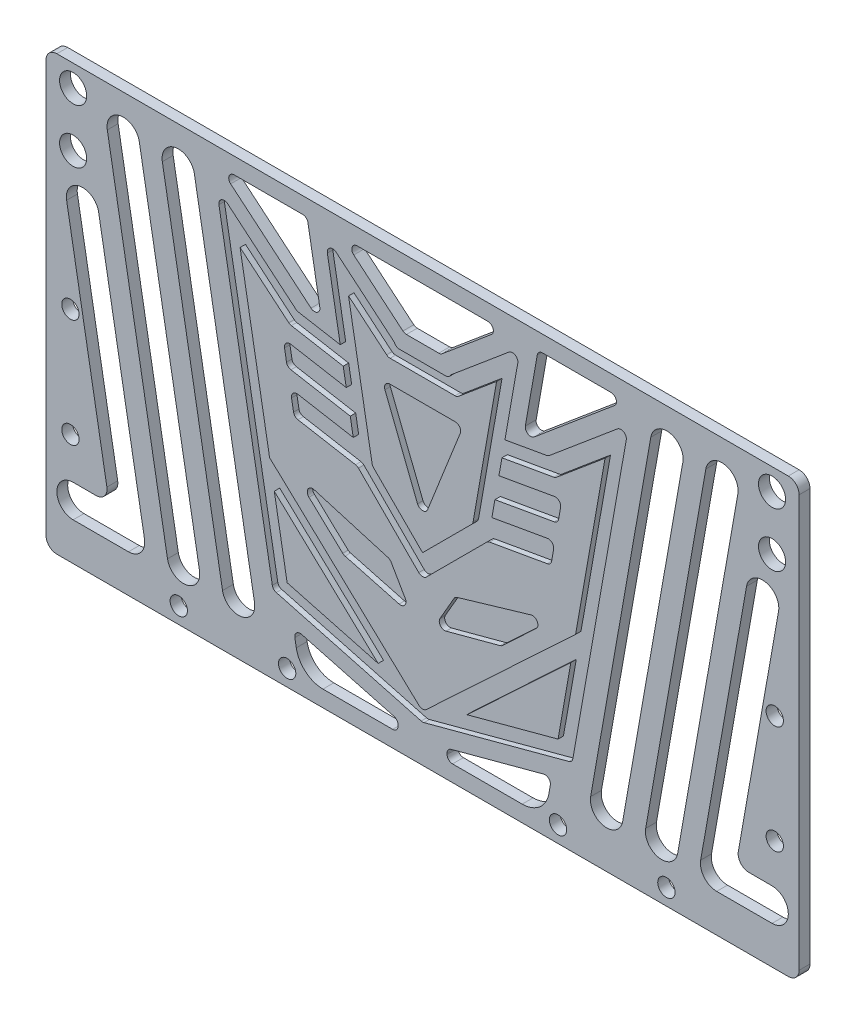
SolidWorks part; units mm, degrees
material "Thornel Mat VMA"
ref_plane "前视基准面" through (0, 0, 0) normal (0, 0, 1) x (1, 0, 0)
ref_plane "上视基准面" through (0, 0, 0) normal (0, 1, 0) x (1, 0, 0)
ref_plane "右视基准面" through (0, 0, 0) normal (1, 0, 0) x (0, 0, -1)
sketch "草图1" plane through (0, 0, 0) normal (0, 0, 1) x (1, 0, 0)
  line L1 (-69.5, 40) -> (69.5, 40)
  line L2 (-69.5, 40) -> (-69.5, -40)
  line L3 (-69.5, -40) -> (69.5, -40)
  line L4 (69.5, 40) -> (69.5, -40)
  line L5 (-69.5, 40) -> (69.5, -40) construction
  line L6 (-69.5, -40) -> (69.5, 40) construction
  point P0 (0, 0)
  dimension "D1" = 139
  dimension "D2" = 80
extrude "凸台-拉伸1" add sketch "草图1" along normal blind 2
sketch "草图2" plane through (0, 0, 0) normal (0, 0, -1) x (-1, 0, 0)
  circle A0 centre (-45, -37) radius 1.6
  circle A1 centre (-25, -37) radius 1.6
  circle A2 centre (25, -37) radius 1.6
  circle A3 centre (45, -37) radius 1.6
  dimension "D1" = 3.2
extrude "切除-拉伸1" cut sketch "草图2" against normal blind 10
sketch "草图3" plane through (0, 0, 0) normal (0, 0, -1) x (-1, 0, 0)
  line L1 (-1.3397, -15) -> (-51.3397, -15)
  line L2 (-1.3397, -15) -> (-18.6603, 15)
  line L6 (-35, 0) -> (-35, 16.5) construction
  line L7 (-35, 0) -> (-49.2894, -8.25) construction
  line L8 (-35, 0) -> (-20.7106, -8.25) construction
  line L9 (-35, 2.6) -> (-30.2, 2.6) construction
  line L10 (-35, 0) -> (-30.2, 0) construction
  line L11 (-35, 0) -> (-35, 6.6) construction
  line L12 (-35, 6.6) -> (-30.2, 6.6) construction
  line L13 (-30.2, 0) -> (-30.2, 6.6) construction
  line L14 (-51.3397, -15) -> (-68.6603, 15)
  line L15 (-18.6603, 15) -> (-68.6603, 15)
  line L16 (-32.3909, -3.9037) -> (-35, 0) construction
  line L17 (-39.6853, -0.3077) -> (-35, 0) construction
  line L18 (-32.9238, 4.2114) -> (-35, 0) construction
  line L19 (-33.3265, -4.3035) -> (-34.5582, -2.4607)
  line L20 (-31.394, -3.5956) -> (-32.8954, -1.3493)
  line L21 (-39.9169, -1.3251) -> (-37.2208, -1.148)
  line L22 (-39.5637, 0.7024) -> (-37.3519, 0.8477)
  line L23 (-33.6891, 4.9207) -> (-34.8838, 2.4973)
  line L24 (-32.1098, 3.6011) -> (-33.0899, 1.6129)
  circle A0 centre (-35, 0) radius 16.5
  arc A3 (-35, 6.6) -> (-30.2, 2.6) centre (-26.586, 11.8168) ccw
  arc A4 (-33.3058, 16.4128) -> (-35, 6.6) centre (-28.6258, 10.5521) ccw
  arc A5 (-21.9598, -10.1096) -> (-30.2, 2.6) centre (-34.9456, -9.5028) ccw
  arc A6 (-21.6332, -9.6736) -> (-29.2842, -3.3) centre (-29.0487, -10.7963) ccw
  arc A7 (-50.2752, -6.2384) -> (-35.1483, -5.4569) centre (-43.2569, 4.7043) ccw
  arc A8 (-29.2842, -3.3) -> (-35.1483, -5.4569) centre (-28.9734, -13.1951) ccw
  arc A9 (-50.061, -6.7391) -> (-40.7158, -3.3) centre (-47.3255, 0.2442) ccw
  arc A10 (-32.765, 16.3479) -> (-39.6517, 2.8569) centre (-26.7975, 4.7985) ccw
  arc A11 (-40.7158, -3.3) -> (-39.6517, 2.8569) centre (-49.4406, 1.3783) ccw
  circle A12 centre (-35, 0) radius 2.5
  point P0 (-10, 0)
  point P43 (-35, 0)
  dimension "D6" = 33
  dimension "D10" = 19.8
  dimension "D11" = 15
  dimension "D12" = 26
  dimension "D16" = 5
  dimension "D2" = 50
  dimension "D3" = 30
  dimension "D4" = 60
  dimension "D5" = 120
  dimension "D7" = 4.8
  dimension "D8" = 6.6
  dimension "D9" = 2.6
  dimension "D14" = 10
  dimension "D15" = 35
  dimension "D17" = 2
  dimension "D18" = 2
  dimension "D19" = 2
  dimension "D13" = 3
extrude "切除-拉伸2" [suppressed] cut sketch "草图3" against normal blind 10 contours A0 L15 L14 L1 | A0 L1 L2 L15 | A12 L23 A3 A4 L15 A10 A11 L22 | A12 L21 A11 A9 A7 A8 L19 | A12 L20 A8 A6 A5 A3 L24
mirror "镜向1" [suppressed] about plane through (0, 0, 0) normal (1, 0, 0)
sketch "草图7" plane through (0, 0, 2) normal (0, 0, 1) x (1, 0, 0)
  line L0 (-7.5, 6.6144) -> (-1.5, 34.9678)
  line L1 (0, 10) -> (0, 51.6967) construction
  line L2 (7.5, 6.6144) -> (1.5, 34.9678)
  line L3 (0, 0) -> (24.9019, 9.0635)
  line L4 (0, 0) -> (72.3407, 0) construction
  line L5 (7.5, 6.6144) -> (4.826, 5.0705)
  line L6 (9.4782, 3.188) -> (6.8042, 1.6441)
  line L7 (0, 0) -> (8.6603, 5) construction
  line L8 (-1.9782, -9.8024) -> (-1.9782, -6.7147)
  line L9 (1.9782, -9.8024) -> (1.9782, -6.7147)
  line L10 (-7.5, 6.6144) -> (-4.826, 5.0705)
  line L11 (1.9782, -9.8024) -> (29.533, -18.783)
  line L12 (9.4782, 3.188) -> (31.033, -16.1849)
  line L13 (-9.4782, 3.188) -> (-31.033, -16.1849)
  line L14 (-1.9782, -9.8024) -> (-29.533, -18.783)
  line L15 (-9.4782, 3.188) -> (-6.8042, 1.6441)
  circle A0 centre (0, 0) radius 35
  circle A1 centre (0, 0) radius 26.5
  circle A2 centre (0, 0) radius 25
  circle A3 centre (0, 0) radius 10
  arc A5 (24.9019, 9.0635) -> (1.5, 34.9678) centre (-4.9044, 5.6594) ccw
  circle A6 centre (0, 0) radius 7
  arc A7 (-4.6017, -26.0974) -> (29.533, -18.783) centre (7.3534, 1.4176) ccw
  arc A8 (-20.3002, 17.0339) -> (-31.033, -16.1849) centre (-2.449, -7.077) ccw
  point P30 (0, 0)
  point P31 (0, 0)
  point P44 (0, 0)
  dimension "D1" = 70
  dimension "D2" = 53
  dimension "D3" = 50
  dimension "D4" = 20
  dimension "D7" = 30
  dimension "D9" = 3
  dimension "D5" = 15
  dimension "D6" = 3
  dimension "D8" = 20
  dimension "D11" = 3
  dimension "D10" = 3
extrude "切除-拉伸3" [suppressed] cut sketch "草图7" against normal blind 3 contours A1 A8 L13 | A1 L13 A0 L14 | A2 L13 A1 L14 | A3 L13 A2 L14 | A6 L15 A3 L8 | A6 L9 A3 L6 | A3 L11 A2 L12 | A2 L11 A1 L12 | A1 L11 A0 L12 | A1 A7 L11 | A6 L5 A3 L10 | A3 L2 A2 L0 | A2 L2 A1 L0 | A1 L2 A0 L0 | A1 A5 L2
sketch "草图8" plane through (0, 0, 2) normal (0, 0, 1) x (1, 0, 0)
  line L0 (-33.6824, 25.9391) -> (-25, -23.3013)
  line L1 (-25, -23.3013) -> (0, -30)
  line L2 (0, -30) -> (25, -23.3013)
  line L3 (25, -23.3013) -> (33.6824, 25.9391)
  line L4 (33.6824, 25.9391) -> (24.4899, 18.2257)
  line L5 (24.4899, 18.2257) -> (11.5, 15.9352)
  line L6 (11.5, 15.9352) -> (13.6634, 28.2047)
  line L7 (13.6634, 28.2047) -> (5, 20.9352)
  line L8 (5, 20.9352) -> (-5, 20.9352)
  line L9 (-5, 20.9352) -> (-13.6634, 28.2047)
  line L10 (-13.6634, 28.2047) -> (-11.5, 15.9352)
  line L11 (-11.5, 15.9352) -> (-24.4899, 18.2257)
  line L12 (-24.4899, 18.2257) -> (-33.6824, 25.9391)
  line L13 (0, 31.1727) -> (0, 81.1727) construction
  line L14 (-69.5, -40) -> (69.5, -40) construction
  line L15 (0, -30) -> (28.5265, -3.3013)
  line L16 (0, -30) -> (-28.5265, -3.3013)
  line L17 (2.0505, -29.4506) -> (28.2373, -4.9416)
  line L18 (8.2018, -27.8023) -> (27.3696, -9.8627)
  line L19 (-2.0505, -29.4506) -> (-28.2373, -4.9416)
  line L20 (-8.2018, -27.8023) -> (-27.3696, -9.8627)
  line L21 (11.5, 15.9352) -> (9.2661, 3.2661)
  line L22 (9.2661, 3.2661) -> (0, -6)
  line L23 (0, -6) -> (-9.2661, 3.2661)
  line L24 (-9.2661, 3.2661) -> (-11.5, 15.9352)
  line L25 (14.644, 16.4896) -> (12.0563, 1.8136)
  line L26 (12.0563, 1.8136) -> (0, -10.2426)
  line L27 (-14.644, 16.4896) -> (-12.0563, 1.8136)
  line L28 (-12.0563, 1.8136) -> (0, -10.2426)
  line L29 (14.089, 13.3417) -> (25.7305, 15.3945)
  line L30 (25.7305, 15.3945) -> (24.9914, 11.2024)
  line L31 (24.9914, 11.2024) -> (13.3498, 9.1497)
  line L32 (12.7954, 6.0057) -> (24.437, 8.0584)
  line L33 (24.437, 8.0584) -> (23.6978, 3.8663)
  line L34 (23.6978, 3.8663) -> (12.0563, 1.8136)
  line L35 (2, -17) -> (14.5573, -13.6362)
  line L36 (14.5573, -13.6362) -> (24.0487, -4.7529)
  line L37 (24.0487, -4.7529) -> (6.0005, -10.0721)
  line L38 (6.0005, -10.0721) -> (2, -17)
  line L39 (0, 0) -> (41.7879, 0) construction
  line L40 (-24.0487, -4.7529) -> (-6.0005, -10.0721)
  line L41 (-14.5573, -13.6362) -> (-24.0487, -4.7529)
  line L42 (-2, -17) -> (-14.5573, -13.6362)
  line L43 (-6.0005, -10.0721) -> (-2, -17)
  line L44 (-23.6978, 3.8663) -> (-12.0563, 1.8136)
  line L45 (-24.437, 8.0584) -> (-23.6978, 3.8663)
  line L46 (-12.7954, 6.0057) -> (-24.437, 8.0584)
  line L47 (-25.7305, 15.3945) -> (-24.9914, 11.2024)
  line L48 (-14.089, 13.3417) -> (-25.7305, 15.3945)
  line L49 (-24.9914, 11.2024) -> (-13.3498, 9.1497)
  line L50 (12.0544, 19.0792) -> (23.1773, 21.0405)
  line L51 (23.1773, 21.0405) -> (38.0681, 33.5354)
  line L52 (38.0681, 33.5354) -> (33.9182, 10)
  line L53 (-33.9182, 10) -> (-30.8719, 10)
  line L54 (-23.1773, 21.0405) -> (-38.0681, 33.5354)
  line L55 (-12.0544, 19.0792) -> (-23.1773, 21.0405)
  line L56 (33.9182, 10) -> (30.8719, 10)
  line L57 (-38.0681, 33.5354) -> (-33.9182, 10)
  line L58 (25, -23.3013) -> (24.4252, -26.5611)
  line L59 (24.4252, -26.5611) -> (2.0505, -32.5564)
  line L60 (2.0505, -29.4506) -> (2.0505, -32.5564)
  line L61 (-25, -23.3013) -> (-24.4252, -26.5611)
  line L62 (-24.4252, -26.5611) -> (-2.0505, -32.5564)
  line L63 (-2.0505, -32.5564) -> (-2.0505, -29.4506)
  line L64 (28.2373, -4.9416) -> (31.8857, -1.527)
  line L65 (31.8857, -1.527) -> (29.1574, -17)
  line L66 (29.1574, -17) -> (26.1111, -17)
  line L67 (-29.1574, -17) -> (-26.1111, -17)
  line L68 (-31.8857, -1.527) -> (-29.1574, -17)
  line L69 (-28.2373, -4.9416) -> (-31.8857, -1.527)
  line L70 (-15.1984, 19.6336) -> (-18.0491, 35.801)
  line L71 (-18.0491, 35.801) -> (-5, 24.8514)
  line L72 (-5, 24.8514) -> (-5, 20.9352)
  line L73 (5, 24.8514) -> (5, 20.9352)
  line L74 (15.1984, 19.6336) -> (18.0491, 35.801)
  line L75 (18.0491, 35.801) -> (5, 24.8514)
  dimension "D1" = 150
  dimension "D2" = 115
  dimension "D3" = 40
  dimension "D4" = 150
  dimension "D5" = 50
  dimension "D6" = 10
  dimension "D7" = 50
  dimension "D8" = 12
  dimension "D9" = 23
  dimension "D10" = 5
  dimension "D11" = 10
  dimension "D12" = 20
  dimension "D13" = 1
  dimension "D14" = 3
  dimension "D15" = 6
  dimension "D16" = 90
  dimension "D17" = 3
  dimension "D18" = 3
  dimension "D19" = 4
  dimension "D20" = 4
  dimension "D21" = 3
  dimension "D22" = 6
  dimension "D23" = 2
  dimension "D24" = 45
  dimension "D25" = 8
  dimension "D26" = 13
  dimension "D27" = 3
  dimension "D28" = 13
  dimension "D29" = 3
  dimension "D30" = 3
  dimension "D31" = 3
  dimension "D32" = 3
  dimension "D33" = 3
  dimension "D34" = 17
  dimension "D35" = 3
  dimension "D36" = 10
  dimension "D37" = 17
extrude "切除-拉伸4" cut sketch "草图8" against normal blind 10
sketch "草图10" plane through (0, 0, 2) normal (0, 0, 1) x (1, 0, 0)
  line L7 (-7.5, 17.9352) -> (7.5, 17.9352)
  line L10 (7.5, 17.9352) -> (0, -1)
  line L11 (0, -1) -> (-7.5, 17.9352)
  line L12 (0, 0) -> (0, 45.0401) construction
  dimension "D1" = 5
  dimension "D2" = 15
  dimension "D3" = 3
extrude "切除-拉伸6" cut sketch "草图10" against normal blind 10
sketch "草图12" plane through (0, 0, 0) normal (0, 0, -1) x (-1, 0, 0)
  line L0 (-45.0817, 33) -> (-33.9731, -30) construction
  line L1 (-42.1273, 33.5209) -> (-31.0187, -29.4791)
  line L2 (-48.0361, 32.4791) -> (-36.9275, -30.5209)
  line L3 (-55.236, 33) -> (-44.1274, -30) construction
  line L4 (-52.2815, 33.5209) -> (-41.1729, -29.4791)
  line L5 (-58.1904, 32.4791) -> (-47.0818, -30.5209)
  line L6 (-62.7453, 18) -> (-54.2816, -30) construction
  line L7 (-59.7909, 18.5209) -> (-51.3272, -29.4791)
  line L8 (-65.6997, 17.4791) -> (-57.8569, -27)
  line L9 (-31.8857, -1.527) -> (-29.1574, -17) construction
  line L10 (69.5, -40) -> (-69.5, -40) construction
  line L11 (-69.5, 40) -> (69.5, 40) construction
  line L12 (-69.5, -40) -> (-69.5, 40) construction
  line L15 (-54.2816, -30) -> (-64.5, -30) construction
  line L16 (-54.2816, -33) -> (-64.5, -33)
  line L18 (-57.8569, -27) -> (-64.5, -27)
  line L19 (0, -52.9402) -> (0, 55.6243) construction
  line L20 (45.0817, 33) -> (33.9731, -30) construction
  line L21 (42.1273, 33.5209) -> (31.0187, -29.4791)
  line L22 (48.0361, 32.4791) -> (36.9275, -30.5209)
  line L23 (55.236, 33) -> (44.1274, -30) construction
  line L24 (52.2815, 33.5209) -> (41.1729, -29.4791)
  line L25 (58.1904, 32.4791) -> (47.0818, -30.5209)
  line L26 (54.2816, -30) -> (64.5, -30) construction
  line L27 (62.7453, 18) -> (54.2816, -30) construction
  line L28 (57.8569, -27) -> (64.5, -27)
  line L29 (54.2816, -33) -> (64.5, -33)
  line L30 (65.6997, 17.4791) -> (57.8569, -27)
  line L31 (59.7909, 18.5209) -> (51.3272, -29.4791)
  arc A0 (-42.1273, 33.5209) -> (-48.0361, 32.4791) centre (-45.0817, 33) ccw
  arc A1 (-36.9275, -30.5209) -> (-31.0187, -29.4791) centre (-33.9731, -30) ccw
  arc A2 (-52.2815, 33.5209) -> (-58.1904, 32.4791) centre (-55.236, 33) ccw
  arc A3 (-47.0818, -30.5209) -> (-41.1729, -29.4791) centre (-44.1274, -30) ccw
  arc A4 (-59.7909, 18.5209) -> (-65.6997, 17.4791) centre (-62.7453, 18) ccw
  arc A5 (-54.2816, -33) -> (-51.3272, -29.4791) centre (-54.2816, -30) ccw
  circle A8 centre (-64.5, 26) radius 2.5
  circle A9 centre (-64.5, 36) radius 2.5
  arc A10 (-54.2816, -33) -> (-51.3272, -29.4791) centre (-54.2816, -30) ccw
  arc A11 (-64.5, -27) -> (-64.5, -33) centre (-64.5, -30) ccw
  arc A12 (42.1273, 33.5209) -> (48.0361, 32.4791) centre (45.0817, 33) cw
  arc A13 (36.9275, -30.5209) -> (31.0187, -29.4791) centre (33.9731, -30) cw
  arc A14 (52.2815, 33.5209) -> (58.1904, 32.4791) centre (55.236, 33) cw
  arc A15 (47.0818, -30.5209) -> (41.1729, -29.4791) centre (44.1274, -30) cw
  arc A16 (64.5, -27) -> (64.5, -33) centre (64.5, -30) cw
  arc A17 (54.2816, -33) -> (51.3272, -29.4791) centre (54.2816, -30) cw
  circle A18 centre (64.5, 36) radius 2.5
  circle A19 centre (64.5, 26) radius 2.5
  arc A20 (54.2816, -33) -> (51.3272, -29.4791) centre (54.2816, -30) cw
  arc A21 (59.7909, 18.5209) -> (65.6997, 17.4791) centre (62.7453, 18) cw
  point P2 (-39.5274, 1.5)
  point P7 (-49.6817, 1.5)
  point P34 (39.5274, 1.5)
  point P48 (49.6817, 1.5)
  dimension "D2" = 3
  dimension "D8" = 5
  dimension "D12" = 2
  dimension "D13" = 3
  dimension "D1" = 10
  dimension "D3" = 7
  dimension "D4" = 4
  dimension "D5" = 4
  dimension "D6" = 4
  dimension "D7" = 22
  dimension "D9" = 5
  dimension "D10" = 10
  dimension "D11" = 4
  dimension "D14" = 45.1652
  dimension "D15" = 6
extrude "切除-拉伸7" cut sketch "草图12" against normal blind 10 contours A21 L31 A17 L29 A16 L28 L30 | A15 L25 A14 L24 | A13 L22 A12 L21 | A18 | A19 | L5 A3 L4 A2 | L2 A1 L1 A0 | A8 | A9 | L18 A11 L16 A5 L7 A4 L8
fillet "圆角2" radius 1 36 edges at (7.5, 17.9352, 1) (-7.5, 17.9352, 1) (0, -1, 1) (33.9182, 10, 1) (30.8719, 10, 1) (38.0681, 33.5354, 1) (18.0491, 35.801, 1) (5, 24.8514, 1) (5, 20.9352, 1) (-5, 20.9352, 1) (-5, 24.8514, 1) (-18.0491, 35.801, 1) (-24.4899, 18.2257, 1) (-38.0681, 33.5354, 1) (-33.9182, 10, 1) (-30.8719, 10, 1) (-24.9914, 11.2024, 1) (-25.7305, 15.3945, 1) (-24.437, 8.0584, 1) (-23.6978, 3.8663, 1) (25.7305, 15.3945, 1) (24.9914, 11.2024, 1) (24.437, 8.0584, 1) (23.6978, 3.8663, 1) (0, -10.2426, 1) (-2, -17, 1) (-14.5573, -13.6362, 1) (-24.0487, -4.7529, 1) (-6.0005, -10.0721, 1) (14.5573, -13.6362, 1) (2, -17, 1) (6.0005, -10.0721, 1) (24.0487, -4.7529, 1) (-23.1773, 21.0405, 1) (23.1773, 21.0405, 1) (24.4899, 18.2257, 1)
sketch "草图16" plane through (0, 0, 0) normal (0, 0, -1) x (-1, 0, 0)
  line L3 (-6.9581, 16.5669) -> (-0.9297, 1.3473)
  line L4 (5.8006, -10.4182) -> (3.2072, -14.9093)
  line L5 (20.0041, -5.9449) -> (6.3839, -9.9591)
  line L6 (14.74, -13.4651) -> (20.9701, -7.6342)
  line L7 (4.332, -16.3753) -> (14.3155, -13.7009)
  line L8 (5.8006, -10.4182) -> (3.2072, -14.9093)
  line L9 (8.2018, -27.8023) -> (27.3696, -9.8627)
  line L10 (25, -23.3013) -> (8.2018, -27.8023)
  line L11 (24.4252, -26.5611) -> (25, -23.3013)
  line L12 (2.0505, -32.5564) -> (24.4252, -26.5611)
  line L13 (2.0505, -29.4506) -> (2.0505, -32.5564)
  line L14 (31.8857, -1.527) -> (2.0505, -29.4506)
  line L15 (29.1574, -17) -> (31.8857, -1.527)
  line L16 (26.1111, -17) -> (29.1574, -17)
  line L17 (27.3696, -9.8627) -> (26.1111, -17)
  line L18 (8.2018, -27.8023) -> (27.3696, -9.8627)
  line L19 (25, -23.3013) -> (8.2018, -27.8023)
  line L20 (24.4252, -26.5611) -> (25, -23.3013)
  line L21 (2.0505, -32.5564) -> (24.4252, -26.5611)
  line L22 (2.0505, -29.4506) -> (2.0505, -32.5564)
  line L23 (31.8857, -1.527) -> (2.0505, -29.4506)
  line L24 (29.1574, -17) -> (31.8857, -1.527)
  line L25 (26.1111, -17) -> (29.1574, -17)
  line L26 (27.3696, -9.8627) -> (26.1111, -17)
  line L27 (20.0041, -5.9449) -> (6.3839, -9.9591)
  line L28 (14.74, -13.4651) -> (20.9701, -7.6342)
  line L29 (4.332, -16.3753) -> (14.3155, -13.7009)
  line L30 (-14.3155, -13.7009) -> (-4.332, -16.3753)
  line L31 (-20.9701, -7.6342) -> (-14.74, -13.4651)
  line L32 (-6.3839, -9.9591) -> (-20.0041, -5.9449)
  line L33 (-3.2072, -14.9093) -> (-5.8006, -10.4182)
  line L34 (-14.3155, -13.7009) -> (-4.332, -16.3753)
  line L35 (-20.9701, -7.6342) -> (-14.74, -13.4651)
  line L36 (-6.3839, -9.9591) -> (-20.0041, -5.9449)
  line L37 (-3.2072, -14.9093) -> (-5.8006, -10.4182)
  line L38 (6.0283, 17.9352) -> (-6.0283, 17.9352)
  line L39 (0.9297, 1.3473) -> (6.9581, 16.5669)
  line L40 (-6.9581, 16.5669) -> (-0.9297, 1.3473)
  line L41 (6.0283, 17.9352) -> (-6.0283, 17.9352)
  line L42 (0.9297, 1.3473) -> (6.9581, 16.5669)
  line L43 (-2.0505, -29.4506) -> (-31.8857, -1.527)
  line L44 (-2.0505, -32.5564) -> (-2.0505, -29.4506)
  line L45 (-24.4252, -26.5611) -> (-2.0505, -32.5564)
  line L46 (-25, -23.3013) -> (-24.4252, -26.5611)
  line L47 (-8.2018, -27.8023) -> (-25, -23.3013)
  line L48 (-27.3696, -9.8627) -> (-8.2018, -27.8023)
  line L49 (-26.1111, -17) -> (-27.3696, -9.8627)
  line L50 (-29.1574, -17) -> (-26.1111, -17)
  line L51 (-31.8857, -1.527) -> (-29.1574, -17)
  line L52 (-2.0505, -29.4506) -> (-31.8857, -1.527)
  line L53 (-2.0505, -32.5564) -> (-2.0505, -29.4506)
  line L54 (-24.4252, -26.5611) -> (-2.0505, -32.5564)
  line L55 (-25, -23.3013) -> (-24.4252, -26.5611)
  line L56 (-8.2018, -27.8023) -> (-25, -23.3013)
  line L57 (-27.3696, -9.8627) -> (-8.2018, -27.8023)
  line L58 (-26.1111, -17) -> (-27.3696, -9.8627)
  line L59 (-29.1574, -17) -> (-26.1111, -17)
  line L60 (-31.8857, -1.527) -> (-29.1574, -17)
  line L96 (22.9134, 20.994) -> (15.1984, 19.6336)
  line L97 (35.9634, 31.7693) -> (23.3826, 21.2127)
  line L98 (34.0639, 10.8264) -> (37.591, 30.8296)
  line L99 (32.0637, 10) -> (33.0791, 10)
  line L100 (33.6824, 25.9391) -> (31.0789, 11.1736)
  line L101 (24.6951, 18.3979) -> (33.6824, 25.9391)
  line L102 (14.644, 16.4896) -> (24.226, 18.1791)
  line L103 (14.089, 13.3417) -> (14.644, 16.4896)
  line L104 (24.3241, 15.1465) -> (14.089, 13.3417)
  line L105 (25.113, 11.892) -> (25.4825, 13.988)
  line L106 (13.3498, 9.1497) -> (24.3018, 11.0808)
  line L107 (12.7954, 6.0057) -> (13.3498, 9.1497)
  line L108 (23.0305, 7.8104) -> (12.7954, 6.0057)
  line L109 (23.8194, 4.5559) -> (24.189, 6.6519)
  line L110 (12.0563, 1.8136) -> (23.0083, 3.7448)
  line L111 (0.7071, -9.5355) -> (12.0563, 1.8136)
  line L112 (-12.0563, 1.8136) -> (-0.7071, -9.5355)
  line L113 (-23.0083, 3.7448) -> (-12.0563, 1.8136)
  line L114 (-24.189, 6.6519) -> (-23.8194, 4.5559)
  line L115 (-12.7954, 6.0057) -> (-23.0305, 7.8104)
  line L116 (-13.3498, 9.1497) -> (-12.7954, 6.0057)
  line L117 (-24.3018, 11.0808) -> (-13.3498, 9.1497)
  line L118 (-25.4825, 13.988) -> (-25.113, 11.892)
  line L119 (-14.089, 13.3417) -> (-24.3241, 15.1465)
  line L120 (-14.644, 16.4896) -> (-14.089, 13.3417)
  line L121 (-24.226, 18.1791) -> (-14.644, 16.4896)
  line L122 (-33.6824, 25.9391) -> (-24.6951, 18.3979)
  line L123 (-31.0789, 11.1736) -> (-33.6824, 25.9391)
  line L124 (-33.0791, 10) -> (-32.0637, 10)
  line L125 (-37.591, 30.8296) -> (-34.0639, 10.8264)
  line L126 (-23.3826, 21.2127) -> (-35.9634, 31.7693)
  line L127 (-15.1984, 19.6336) -> (-22.9134, 20.994)
  line L128 (-17.5721, 33.0952) -> (-15.1984, 19.6336)
  line L129 (-5.3572, 25.1512) -> (-15.9445, 34.0349)
  line L130 (-5, 23.0797) -> (-5, 24.3851)
  line L131 (-13.6634, 28.2047) -> (-6.6428, 22.3137)
  line L132 (-9.2661, 3.2661) -> (-13.6634, 28.2047)
  line L133 (0, -6) -> (-9.2661, 3.2661)
  line L134 (9.2661, 3.2661) -> (0, -6)
  line L135 (13.6634, 28.2047) -> (9.2661, 3.2661)
  line L136 (6.6428, 22.3137) -> (13.6634, 28.2047)
  line L137 (5, 24.3851) -> (5, 23.0797)
  line L138 (15.9445, 34.0349) -> (5.3572, 25.1512)
  line L139 (15.1984, 19.6336) -> (17.5721, 33.0952)
  line L140 (22.9134, 20.994) -> (15.1984, 19.6336)
  line L141 (35.9634, 31.7693) -> (23.3826, 21.2127)
  line L142 (34.0639, 10.8264) -> (37.591, 30.8296)
  line L143 (32.0637, 10) -> (33.0791, 10)
  line L144 (33.6824, 25.9391) -> (31.0789, 11.1736)
  line L145 (24.6951, 18.3979) -> (33.6824, 25.9391)
  line L146 (14.644, 16.4896) -> (24.226, 18.1791)
  line L147 (14.089, 13.3417) -> (14.644, 16.4896)
  line L148 (24.3241, 15.1465) -> (14.089, 13.3417)
  line L149 (25.113, 11.892) -> (25.4825, 13.988)
  line L150 (13.3498, 9.1497) -> (24.3018, 11.0808)
  line L151 (12.7954, 6.0057) -> (13.3498, 9.1497)
  line L152 (23.0305, 7.8104) -> (12.7954, 6.0057)
  line L153 (23.8194, 4.5559) -> (24.189, 6.6519)
  line L154 (12.0563, 1.8136) -> (23.0083, 3.7448)
  line L155 (0.7071, -9.5355) -> (12.0563, 1.8136)
  line L156 (-12.0563, 1.8136) -> (-0.7071, -9.5355)
  line L157 (-23.0083, 3.7448) -> (-12.0563, 1.8136)
  line L158 (-24.189, 6.6519) -> (-23.8194, 4.5559)
  line L159 (-12.7954, 6.0057) -> (-23.0305, 7.8104)
  line L160 (-13.3498, 9.1497) -> (-12.7954, 6.0057)
  line L161 (-24.3018, 11.0808) -> (-13.3498, 9.1497)
  line L162 (-25.4825, 13.988) -> (-25.113, 11.892)
  line L163 (-14.089, 13.3417) -> (-24.3241, 15.1465)
  line L164 (-14.644, 16.4896) -> (-14.089, 13.3417)
  line L165 (-24.226, 18.1791) -> (-14.644, 16.4896)
  line L166 (-33.6824, 25.9391) -> (-24.6951, 18.3979)
  line L167 (-31.0789, 11.1736) -> (-33.6824, 25.9391)
  line L168 (-33.0791, 10) -> (-32.0637, 10)
  line L169 (-37.591, 30.8296) -> (-34.0639, 10.8264)
  line L170 (-23.3826, 21.2127) -> (-35.9634, 31.7693)
  line L171 (-15.1984, 19.6336) -> (-22.9134, 20.994)
  line L172 (-17.5721, 33.0952) -> (-15.1984, 19.6336)
  line L173 (-5.3572, 25.1512) -> (-15.9445, 34.0349)
  line L174 (-5, 23.0797) -> (-5, 24.3851)
  line L175 (-13.6634, 28.2047) -> (-6.6428, 22.3137)
  line L176 (-9.2661, 3.2661) -> (-13.6634, 28.2047)
  line L177 (0, -6) -> (-9.2661, 3.2661)
  line L178 (9.2661, 3.2661) -> (0, -6)
  line L179 (13.6634, 28.2047) -> (9.2661, 3.2661)
  line L180 (6.6428, 22.3137) -> (13.6634, 28.2047)
  line L181 (5, 24.3851) -> (5, 23.0797)
  line L182 (15.9445, 34.0349) -> (5.3572, 25.1512)
  line L183 (15.1984, 19.6336) -> (17.5721, 33.0952)
  arc A3 (-6.0283, 17.9352) -> (-6.9581, 16.5669) centre (-6.0283, 16.9352) ccw
  arc A4 (6.3839, -9.9591) -> (5.8006, -10.4182) centre (6.6666, -10.9183) ccw
  arc A5 (20.9701, -7.6342) -> (20.0041, -5.9449) centre (20.2867, -6.9041) ccw
  arc A6 (14.3155, -13.7009) -> (14.74, -13.4651) centre (14.0567, -12.735) ccw
  arc A7 (3.2072, -14.9093) -> (4.332, -16.3753) centre (4.0732, -15.4094) ccw
  arc A8 (6.3839, -9.9591) -> (5.8006, -10.4182) centre (6.6666, -10.9183) ccw
  arc A9 (20.9701, -7.6342) -> (20.0041, -5.9449) centre (20.2867, -6.9041) ccw
  arc A10 (14.3155, -13.7009) -> (14.74, -13.4651) centre (14.0567, -12.735) ccw
  arc A11 (3.2072, -14.9093) -> (4.332, -16.3753) centre (4.0732, -15.4094) ccw
  arc A12 (-14.74, -13.4651) -> (-14.3155, -13.7009) centre (-14.0567, -12.735) ccw
  arc A13 (-20.0041, -5.9449) -> (-20.9701, -7.6342) centre (-20.2867, -6.9041) ccw
  arc A14 (-5.8006, -10.4182) -> (-6.3839, -9.9591) centre (-6.6666, -10.9183) ccw
  arc A15 (-4.332, -16.3753) -> (-3.2072, -14.9093) centre (-4.0732, -15.4094) ccw
  arc A16 (-14.74, -13.4651) -> (-14.3155, -13.7009) centre (-14.0567, -12.735) ccw
  arc A17 (-20.0041, -5.9449) -> (-20.9701, -7.6342) centre (-20.2867, -6.9041) ccw
  arc A18 (-5.8006, -10.4182) -> (-6.3839, -9.9591) centre (-6.6666, -10.9183) ccw
  arc A19 (-4.332, -16.3753) -> (-3.2072, -14.9093) centre (-4.0732, -15.4094) ccw
  arc A20 (6.9581, 16.5669) -> (6.0283, 17.9352) centre (6.0283, 16.9352) ccw
  arc A21 (-0.9297, 1.3473) -> (0.9297, 1.3473) centre (0, 1.7155) ccw
  arc A22 (-6.0283, 17.9352) -> (-6.9581, 16.5669) centre (-6.0283, 16.9352) ccw
  arc A23 (6.9581, 16.5669) -> (6.0283, 17.9352) centre (6.0283, 16.9352) ccw
  arc A24 (-0.9297, 1.3473) -> (0.9297, 1.3473) centre (0, 1.7155) ccw
  arc A41 (22.9134, 20.994) -> (23.3826, 21.2127) centre (22.7398, 21.9788) ccw
  arc A42 (37.591, 30.8296) -> (35.9634, 31.7693) centre (36.6062, 31.0033) ccw
  arc A43 (33.0791, 10) -> (34.0639, 10.8264) centre (33.0791, 11) ccw
  arc A44 (31.0789, 11.1736) -> (32.0637, 10) centre (32.0637, 11) ccw
  arc A45 (24.226, 18.1791) -> (24.6951, 18.3979) centre (24.0523, 19.1639) ccw
  arc A46 (25.4825, 13.988) -> (24.3241, 15.1465) centre (24.4977, 14.1617) ccw
  arc A47 (24.3018, 11.0808) -> (25.113, 11.892) centre (24.1282, 12.0656) ccw
  arc A48 (24.189, 6.6519) -> (23.0305, 7.8104) centre (23.2042, 6.8256) ccw
  arc A49 (23.0083, 3.7448) -> (23.8194, 4.5559) centre (22.8346, 4.7296) ccw
  arc A50 (-0.7071, -9.5355) -> (0.7071, -9.5355) centre (0, -8.8284) ccw
  arc A51 (-23.8194, 4.5559) -> (-23.0083, 3.7448) centre (-22.8346, 4.7296) ccw
  arc A52 (-23.0305, 7.8104) -> (-24.189, 6.6519) centre (-23.2042, 6.8256) ccw
  arc A53 (-25.113, 11.892) -> (-24.3018, 11.0808) centre (-24.1282, 12.0656) ccw
  arc A54 (-24.3241, 15.1465) -> (-25.4825, 13.988) centre (-24.4977, 14.1617) ccw
  arc A55 (-24.6951, 18.3979) -> (-24.226, 18.1791) centre (-24.0523, 19.1639) ccw
  arc A56 (-32.0637, 10) -> (-31.0789, 11.1736) centre (-32.0637, 11) ccw
  arc A57 (-34.0639, 10.8264) -> (-33.0791, 10) centre (-33.0791, 11) ccw
  arc A58 (-35.9634, 31.7693) -> (-37.591, 30.8296) centre (-36.6062, 31.0033) ccw
  arc A59 (-23.3826, 21.2127) -> (-22.9134, 20.994) centre (-22.7398, 21.9788) ccw
  arc A60 (-15.9445, 34.0349) -> (-17.5721, 33.0952) centre (-16.5872, 33.2689) ccw
  arc A61 (-5, 24.3851) -> (-5.3572, 25.1512) centre (-6, 24.3851) ccw
  arc A62 (-6.6428, 22.3137) -> (-5, 23.0797) centre (-6, 23.0797) ccw
  arc A63 (5, 23.0797) -> (6.6428, 22.3137) centre (6, 23.0797) ccw
  arc A64 (5.3572, 25.1512) -> (5, 24.3851) centre (6, 24.3851) ccw
  arc A65 (17.5721, 33.0952) -> (15.9445, 34.0349) centre (16.5872, 33.2689) ccw
  arc A66 (22.9134, 20.994) -> (23.3826, 21.2127) centre (22.7398, 21.9788) ccw
  arc A67 (37.591, 30.8296) -> (35.9634, 31.7693) centre (36.6062, 31.0033) ccw
  arc A68 (33.0791, 10) -> (34.0639, 10.8264) centre (33.0791, 11) ccw
  arc A69 (31.0789, 11.1736) -> (32.0637, 10) centre (32.0637, 11) ccw
  arc A70 (24.226, 18.1791) -> (24.6951, 18.3979) centre (24.0523, 19.1639) ccw
  arc A71 (25.4825, 13.988) -> (24.3241, 15.1465) centre (24.4977, 14.1617) ccw
  arc A72 (24.3018, 11.0808) -> (25.113, 11.892) centre (24.1282, 12.0656) ccw
  arc A73 (24.189, 6.6519) -> (23.0305, 7.8104) centre (23.2042, 6.8256) ccw
  arc A74 (23.0083, 3.7448) -> (23.8194, 4.5559) centre (22.8346, 4.7296) ccw
  arc A75 (-0.7071, -9.5355) -> (0.7071, -9.5355) centre (0, -8.8284) ccw
  arc A76 (-23.8194, 4.5559) -> (-23.0083, 3.7448) centre (-22.8346, 4.7296) ccw
  arc A77 (-23.0305, 7.8104) -> (-24.189, 6.6519) centre (-23.2042, 6.8256) ccw
  arc A78 (-25.113, 11.892) -> (-24.3018, 11.0808) centre (-24.1282, 12.0656) ccw
  arc A79 (-24.3241, 15.1465) -> (-25.4825, 13.988) centre (-24.4977, 14.1617) ccw
  arc A80 (-24.6951, 18.3979) -> (-24.226, 18.1791) centre (-24.0523, 19.1639) ccw
  arc A81 (-32.0637, 10) -> (-31.0789, 11.1736) centre (-32.0637, 11) ccw
  arc A82 (-34.0639, 10.8264) -> (-33.0791, 10) centre (-33.0791, 11) ccw
  arc A83 (-35.9634, 31.7693) -> (-37.591, 30.8296) centre (-36.6062, 31.0033) ccw
  arc A84 (-23.3826, 21.2127) -> (-22.9134, 20.994) centre (-22.7398, 21.9788) ccw
  arc A85 (-15.9445, 34.0349) -> (-17.5721, 33.0952) centre (-16.5872, 33.2689) ccw
  arc A86 (-5, 24.3851) -> (-5.3572, 25.1512) centre (-6, 24.3851) ccw
  arc A87 (-6.6428, 22.3137) -> (-5, 23.0797) centre (-6, 23.0797) ccw
  arc A88 (5, 23.0797) -> (6.6428, 22.3137) centre (6, 23.0797) ccw
  arc A89 (5.3572, 25.1512) -> (5, 24.3851) centre (6, 24.3851) ccw
  arc A90 (17.5721, 33.0952) -> (15.9445, 34.0349) centre (16.5872, 33.2689) ccw
  dimension "D1" = 0
  dimension "D2" = 0
  dimension "D3" = 0
  dimension "D4" = 0
  dimension "D5" = 0
  dimension "D6" = 0
extrude "凸台-拉伸7" add sketch "草图16" against normal blind 1
sketch "草图17" plane through (0, 0, 2) normal (0, 0, 1) x (1, 0, 0)
  line L0 (-33.6824, 25.9391) -> (-36.6368, 25.4182)
  line L1 (-37.591, 30.8296) -> (-34.0639, 10.8264) construction
  line L2 (-36.6368, 25.4182) -> (-27.6225, -25.7044)
  line L3 (-27.6225, -25.7044) -> (-24.4252, -26.5611)
  line L4 (-24.4252, -26.5611) -> (-33.6824, 25.9391)
  line L5 (2.0505, -29.4506) -> (0, -31.3697)
  line L6 (0, -31.3697) -> (-2.0505, -29.4506)
  line L7 (-2.0505, -29.4506) -> (-2.0505, -32.5564)
  line L8 (-2.0505, -32.5564) -> (0, -33.1058)
  line L9 (0, -33.1058) -> (2.0505, -32.5564)
  line L10 (2.0505, -32.5564) -> (2.0505, -29.4506)
  line L11 (-6, 22.0797) -> (6, 22.0797)
  line L12 (-5, 24.3851) -> (5, 24.3851)
  line L13 (-6, 22.0797) -> (-6, 24.3851)
  line L14 (-6, 24.3851) -> (-5, 24.3851)
  line L15 (6, 22.0797) -> (6, 24.3851)
  line L16 (6, 24.3851) -> (5, 24.3851)
  line L17 (-24.4252, -26.5611) -> (-2.0505, -32.5564) construction
  line L18 (24.4252, -26.5611) -> (2.0505, -32.5564) construction
  line L19 (-2.0505, -29.4506) -> (-31.8857, -1.527) construction
  line L20 (2.0505, -29.4506) -> (31.8857, -1.527) construction
  line L21 (0, -17.3503) -> (0, 60.5863) construction
  line L22 (24.4252, -26.5611) -> (33.6824, 25.9391)
  line L23 (36.6368, 25.4182) -> (27.6225, -25.7044)
  line L24 (27.6225, -25.7044) -> (24.4252, -26.5611)
  line L25 (33.6824, 25.9391) -> (36.6368, 25.4182)
  arc A0 (-6.6428, 22.3137) -> (-5, 23.0797) centre (-6, 23.0797) ccw construction
  arc A1 (-6.6428, 22.3137) -> (-5, 23.0797) centre (-6, 23.0797) ccw construction
  arc A2 (5, 23.0797) -> (6.6428, 22.3137) centre (6, 23.0797) ccw construction
extrude "切除-拉伸9" cut sketch "草图17" against normal blind 1
fillet "圆角6" radius 1 10 edges at (0, -31.3697, 1.5) (-5, 24.3851, 1.5) (5, 24.3851, 1.5) (27.6225, -25.7044, 1.5) (0, -33.1058, 1.5) (-27.6225, -25.7044, 1.5) (9.2661, 3.2661, 1.5) (12.0563, 1.8136, 1.5) (-9.2661, 3.2661, 1.5) (-12.0563, 1.8136, 1.5)
fillet "圆角7" radius 2 6 edges at (-57.8569, -27, 1) (57.8569, -27, 1) (69.5, -40, 1) (-69.5, 40, 1) (69.5, 40, 1) (-69.5, -40, 1)
sketch "草图19" plane through (0, 0, 2) normal (0, 0, 1) x (1, 0, 0)
  line L0 (-21.1611, 36.1736) -> (-18.9668, 23.7291)
  line L1 (-20.5944, 22.7894) -> (-35.4252, 35.234)
  line L2 (-34.7824, 37) -> (-22.146, 37)
  line L3 (-12.7062, 35.234) -> (-3.6312, 27.6191)
  line L4 (-2.9884, 27.3851) -> (2.9884, 27.3851)
  line L5 (3.6312, 27.6191) -> (12.7062, 35.234)
  line L6 (12.0635, 37) -> (-12.0635, 37)
  line L7 (-15.1984, 19.6336) -> (-17.5721, 33.0952) construction
  line L8 (-23.3826, 21.2127) -> (-35.9634, 31.7693) construction
  line L9 (-15.9445, 34.0349) -> (-5.3572, 25.1512) construction
  line L10 (4.2679, 24.3851) -> (-4.2679, 24.3851) construction
  line L11 (15.9445, 34.0349) -> (5.3572, 25.1512) construction
  line L12 (-15.1984, 19.6336) -> (-17.5721, 33.0952) construction
  line L13 (67.5, 40) -> (-67.5, 40) construction
  line L14 (-15.9445, 34.0349) -> (-5.3572, 25.1512) construction
  line L15 (5.3572, 25.1512) -> (15.9445, 34.0349) construction
  line L16 (0, 0) -> (0, 53.6383) construction
  line L17 (20.5944, 22.7894) -> (35.4252, 35.234)
  line L18 (21.1611, 36.1736) -> (18.9668, 23.7291)
  line L19 (34.7824, 37) -> (22.146, 37)
  line L20 (-22.5845, -37) -> (-23.5778, -31.3668)
  line L21 (-22.3342, -30.2272) -> (-5.2631, -34.8014)
  line L22 (-5.522, -37) -> (-22.5845, -37)
  line L23 (-27.0072, -25.8693) -> (-0.2588, -33.0365) construction
  line L24 (-37.591, 30.8296) -> (-27.7332, -25.077) construction
  line L25 (-0.2588, -33.0365) -> (-27.0072, -25.8693) construction
  line L26 (-67.5, -40) -> (67.5, -40) construction
  line L27 (-4.522, -36) -> (-4.522, -35.7673)
  line L28 (4.522, -36) -> (4.522, -35.7673)
  line L29 (5.522, -37) -> (22.5845, -37)
  line L30 (22.3342, -30.2272) -> (5.2631, -34.8014)
  line L31 (22.5845, -37) -> (23.5778, -31.3668)
  arc A0 (21.1611, 36.1736) -> (22.146, 37) centre (22.146, 36) cw
  arc A1 (35.4252, 35.234) -> (34.7824, 37) centre (34.7824, 36) ccw
  arc A2 (20.5944, 22.7894) -> (18.9668, 23.7291) centre (19.9516, 23.5555) cw
  arc A3 (12.7062, 35.234) -> (12.0635, 37) centre (12.0635, 36) ccw
  arc A4 (2.9884, 27.3851) -> (3.6312, 27.6191) centre (2.9884, 28.3851) ccw
  arc A5 (-3.6312, 27.6191) -> (-2.9884, 27.3851) centre (-2.9884, 28.3851) ccw
  arc A6 (-12.7062, 35.234) -> (-12.0635, 37) centre (-12.0635, 36) cw
  arc A7 (-35.4252, 35.234) -> (-34.7824, 37) centre (-34.7824, 36) cw
  arc A8 (-18.9668, 23.7291) -> (-20.5944, 22.7894) centre (-19.9516, 23.5555) cw
  arc A9 (-21.1611, 36.1736) -> (-22.146, 37) centre (-22.146, 36) ccw
  arc A10 (22.3342, -30.2272) -> (23.5778, -31.3668) centre (22.593, -31.1932) cw
  arc A12 (4.522, -35.7673) -> (5.2631, -34.8014) centre (5.522, -35.7673) cw
  arc A13 (-4.522, -35.7673) -> (-5.2631, -34.8014) centre (-5.522, -35.7673) ccw
  arc A14 (-4.522, -36) -> (-5.522, -37) centre (-5.522, -36) cw
  arc A15 (4.522, -36) -> (5.522, -37) centre (5.522, -36) ccw
  arc A16 (-23.5778, -31.3668) -> (-22.3342, -30.2272) centre (-22.593, -31.1932) cw
  point P33 (21.3069, 37)
  point P36 (37.5299, 37)
  point P39 (18.4897, 21.0234)
  point P50 (-37.5299, 37)
  point P53 (-18.4897, 21.0234)
  point P56 (-21.3069, 37)
  point P75 (23.8504, -29.821)
  point P78 (22.5845, -37)
  point P81 (4.522, -35)
  point P84 (-4.522, -35)
  point P87 (-4.522, -37)
  point P90 (4.522, -37)
  point P93 (-23.8504, -29.821)
  point P96 (-22.5845, -37)
  dimension "D7" = 1
  dimension "D12" = 1
  dimension "D1" = 3
  dimension "D2" = 3
  dimension "D3" = 3
  dimension "D4" = 3
  dimension "D5" = 3
  dimension "D6" = 3
  dimension "D8" = 3
  dimension "D9" = 3
  dimension "D10" = 3
  dimension "D11" = 2
extrude "切除-拉伸11" cut sketch "草图19" against normal blind 10
fillet "圆角8" radius 5 2 edges at (22.5845, -37, 1) (-22.5845, -37, 1)
sketch "草图20" plane through (0, 0, 0) normal (0, 0, -1) x (-1, 0, 0)
  line L0 (0, -46.5726) -> (0, 32.3112) construction
  circle A0 centre (-65, 0.409) radius 1.6
  circle A1 centre (-65, -19.591) radius 1.6
  circle A2 centre (65, -19.591) radius 1.6
  circle A3 centre (65, 0.409) radius 1.6
  dimension "D1" = 3.2
extrude "切除-拉伸12" cut sketch "草图20" against normal blind 10
